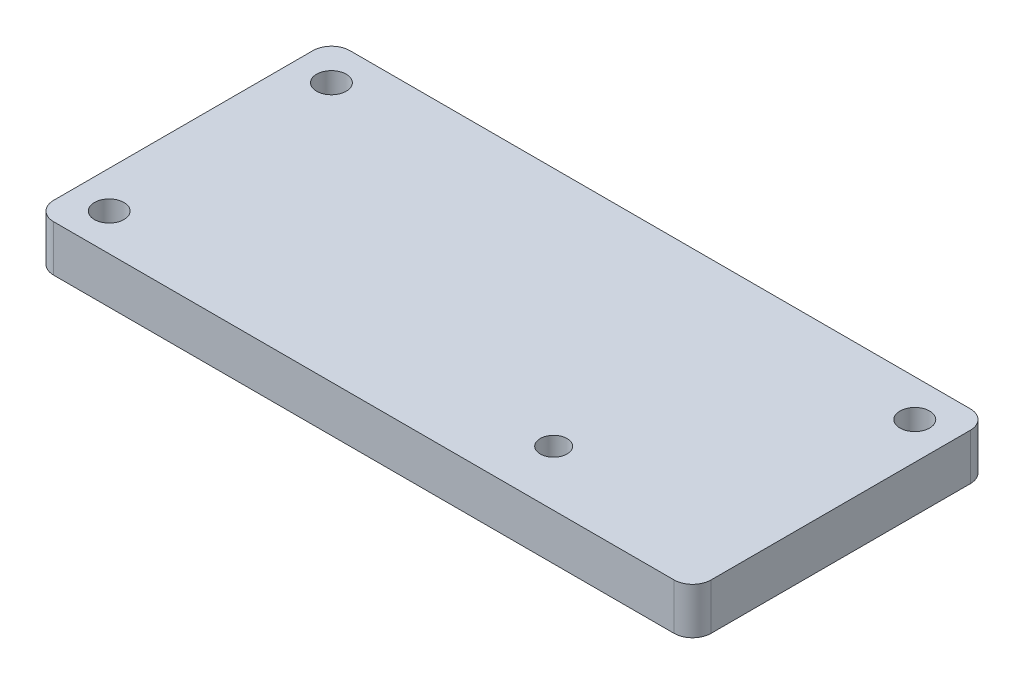
SolidWorks part; units mm, degrees
ref_plane "前视基准面" through (0, 0, 0) normal (0, 0, 1) x (1, 0, 0)
ref_plane "上视基准面" through (0, 0, 0) normal (0, 1, 0) x (1, 0, 0)
ref_plane "右视基准面" through (0, 0, 0) normal (1, 0, 0) x (0, 0, -1)
other "Configuration Table"
sketch "草图1" plane through (0, 0, 0) normal (0, 1, 0) x (1, 0, 0)
  line L1 (-35.5, -16) -> (35.5, -16)
  line L2 (-35.5, -16) -> (-35.5, 16)
  line L3 (-35.5, 16) -> (35.5, 16)
  line L4 (35.5, -16) -> (35.5, 16)
  line L5 (-35.5, -16) -> (35.5, 16) construction
  line L6 (-35.5, 16) -> (35.5, -16) construction
  circle A0 centre (14.5, -10) radius 1.45
  point P0 (0, 0)
  dimension "D5" = 2.9
  dimension "D1" = 71
  dimension "D2" = 32
  dimension "D3" = 26
  dimension "D4" = 21
extrude "凸台-拉伸1" add sketch "草图1" along normal blind 5
sketch "草图2" plane through (0, 5, 0) normal (0, 1, 0) x (1, 0, 0)
  line L0 (-35.5, 16) -> (-35.5, -16) construction
  line L1 (-31.5, 12) -> (31.5, 12) construction
  line L2 (-31.5, 12) -> (-31.5, -12) construction
  line L3 (-31.5, -12) -> (31.5, -12) construction
  line L4 (31.5, 12) -> (31.5, -12) construction
  line L5 (35.5, 16) -> (-35.5, 16) construction
  circle A0 centre (-31.5, 12) radius 1.6
  circle A1 centre (-31.5, -12) radius 1.6
  circle A2 centre (31.5, 12) radius 1.6
  dimension "D5" = 3.2
  dimension "D1" = 63
  dimension "D2" = 24
  dimension "D3" = 4
  dimension "D4" = 4
extrude "切除-拉伸1" cut sketch "草图2" against normal blind 5
fillet "圆角1" radius 2 4 edges at (35.5, 2.5, 16) (35.5, 2.5, -16) (-35.5, 2.5, -16) (-35.5, 2.5, 16)
